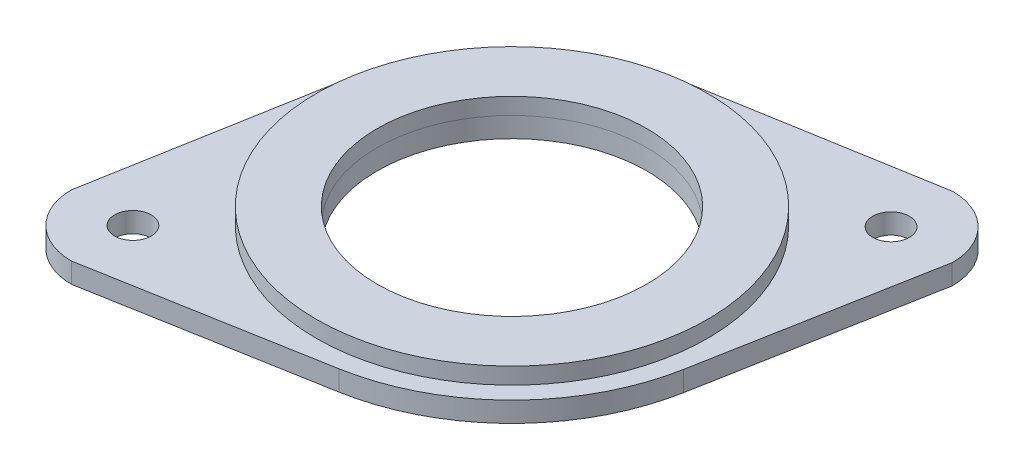
SolidWorks part; units mm, degrees
ref_plane "Front Plane" through (0, 0, 0) normal (0, 0, 1) x (1, 0, 0)
ref_plane "Top Plane" through (0, 0, 0) normal (0, 1, 0) x (1, 0, 0)
ref_plane "Right Plane" through (0, 0, 0) normal (1, 0, 0) x (0, 0, -1)
sketch "Sketch1" plane through (0, 0, 0) normal (0, 1, 0) x (1, 0, 0)
  line L0 (-15500, -15500) -> (-25260.7053, -15500) construction
  line L1 (-15500, -15500) -> (-23515.4297, -7484.5703) construction
  line L2 (0, 0) -> (-17500, 0) construction
  line L3 (20632.5401, 15369.92) -> (17209.3057, -3176.444)
  line L4 (-15500, -20534.9982) -> (3067.6267, -17229.0356)
  line L5 (0, 0) -> (-19120.8905, 19242.1088) construction
  line L6 (15597.6424, 15401.7386) -> (7633.0262, 23467.6615) construction
  line L7 (-20534.9982, -15500) -> (-17229.0356, 3067.6267)
  line L8 (0, 0) -> (19120.8905, -18999.6722) construction
  line L9 (15597.6424, 15401.7386) -> (15659.325, 25162.249) construction
  line L10 (15629.461, 20436.6362) -> (-2958.6869, 17248.0773)
  arc A0 (-2958.6869, 17248.0773) -> (-17229.0356, 3067.6267) centre (0, 0) ccw
  arc A1 (-20534.9982, -15500) -> (-15500, -20534.9982) centre (-15500, -15500) ccw
  arc A2 (17209.3057, -3176.444) -> (12256.2633, -12491.3574) centre (0, 0) cw
  arc A3 (3067.6267, -17229.0356) -> (12413.6548, -12334.9575) centre (0, 0) ccw
  arc A4 (15629.461, 20436.6362) -> (20632.5401, 15369.92) centre (15597.6424, 15401.7386) cw
  circle A5 centre (-15500, -15500) radius 1500
  circle A6 centre (15597.6424, 15401.7386) radius 1500
  circle A7 centre (0, 0) radius 11025
  dimension "D1" = 45
extrude "Boss-Extrude1" add sketch "Sketch1" along normal blind 1650 contours A4 L10 A0 L7 A1 L4 A3 A2 L3 A7 A6 A5
sketch "Sketch2" plane through (0, 1650, 0) normal (0, 1, 0) x (1, 0, 0)
  circle A0 centre (0, 0) radius 11025
  circle A1 centre (0, 0) radius 16000
extrude "Boss-Extrude2" add sketch "Sketch2" along normal blind 1350 separate body
scale "Scale2" bodies to scale 102 101 scale about origin uniform scaling yes scale factor 0.001
